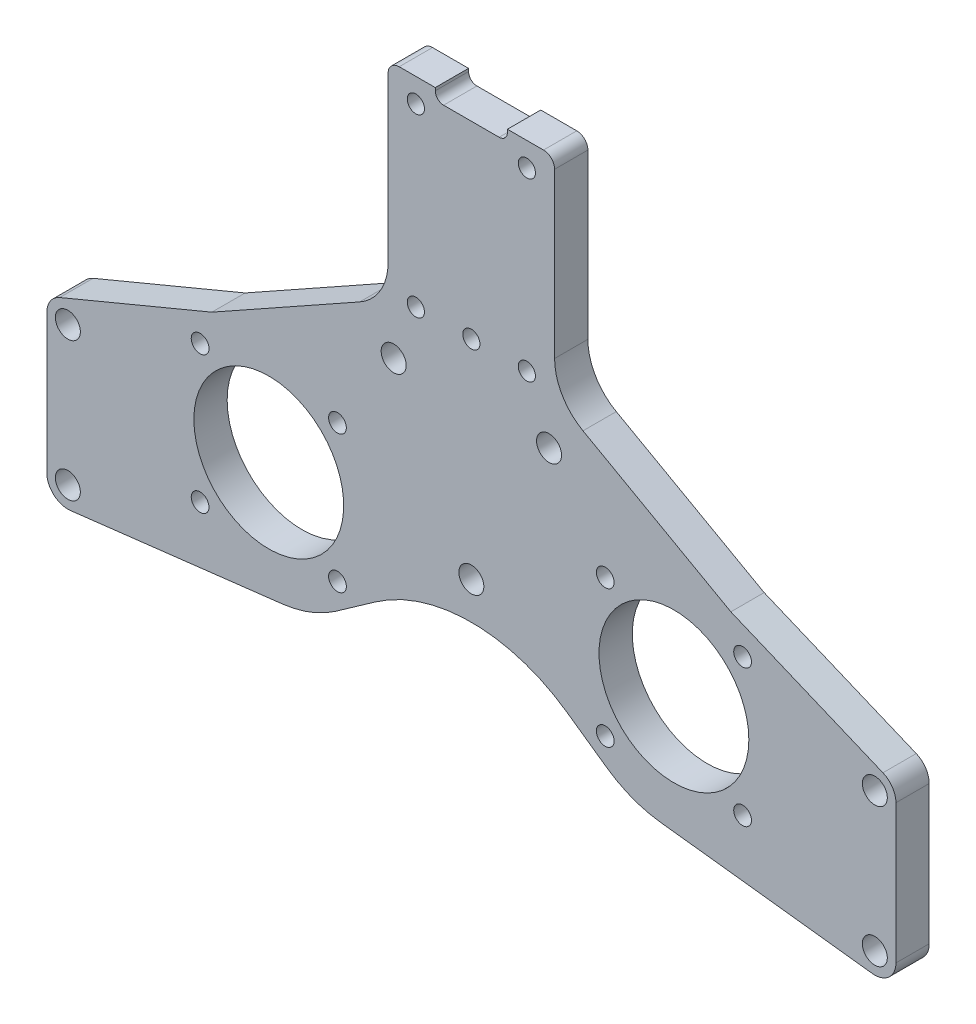
SolidWorks part; units mm, degrees
ref_plane "前视基准面" through (0, 0, 0) normal (0, 0, 1) x (1, 0, 0)
ref_plane "上视基准面" through (0, 0, 0) normal (0, 1, 0) x (1, 0, 0)
ref_plane "右视基准面" through (0, 0, 0) normal (1, 0, 0) x (0, 0, -1)
sketch "草图1" plane through (0, 0, 0) normal (0, 0, 1) x (1, 0, 0)
  line L0 (0, 0) -> (0, 27.5) construction
  line L1 (-14, 27.5) -> (14, 27.5) construction
  line L2 (-36.5, 0) -> (36.5, 0) construction
  line L3 (-20.1139, 33.2452) -> (-46.7609, 18.3225)
  line L4 (-24.4178, -17.1762) -> (-17.2603, -12.1414)
  line L5 (17.2603, -12.1414) -> (24.4178, -17.1762)
  line L6 (46.7609, 18.3225) -> (20.1139, 33.2452)
  line L7 (15, 41.9702) -> (15, 71.5)
  line L8 (13, 73.5) -> (-13, 73.5)
  line L9 (-15, 71.5) -> (-15, 41.9702)
  line L10 (0, 27.5) -> (0, 73.5) construction
  line L11 (24.1256, 12.3744) -> (36.5, 0) construction
  line L13 (10, 69.2) -> (-10, 69.2) construction
  line L14 (10, 69.2) -> (10, 37.5) construction
  line L15 (10, 37.5) -> (-10, 37.5) construction
  line L16 (-10, 69.2) -> (-10, 37.5) construction
  line L17 (10, 69.2) -> (-10, 37.5) construction
  line L18 (10, 37.5) -> (-10, 69.2) construction
  circle A0 centre (-14, 27.5) radius 2.25
  circle A1 centre (14, 27.5) radius 2.25
  circle A3 centre (36.5, 0) radius 13.5
  circle A6 centre (36.5, 0) radius 17.5 construction
  circle A7 centre (24.1256, 12.3744) radius 1.6
  circle A8 centre (48.8744, 12.3744) radius 1.6
  circle A9 centre (48.8744, -12.3744) radius 1.6
  circle A10 centre (24.1256, -12.3744) radius 1.6
  circle A11 centre (0, 0) radius 2.25
  circle A12 centre (-24.1256, -12.3744) radius 1.6
  circle A13 centre (-48.8744, -12.3744) radius 1.6
  circle A14 centre (-48.8744, 12.3744) radius 1.6
  circle A15 centre (-24.1256, 12.3744) radius 1.6
  circle A16 centre (-36.5, 0) radius 13.5
  arc A17 (24.4178, -17.1762) -> (46.7609, 18.3225) centre (36.5, 0) ccw
  arc A18 (-46.7609, 18.3225) -> (-24.4178, -17.1762) centre (-36.5, 0) ccw
  arc A19 (-17.2603, -12.1414) -> (17.2603, -12.1414) centre (0, -36.6787) cw
  arc A20 (20.1139, 33.2452) -> (15, 41.9702) centre (25, 41.9702) cw
  arc A21 (-20.1139, 33.2452) -> (-15, 41.9702) centre (-25, 41.9702) ccw
  arc A22 (-13, 73.5) -> (-15, 71.5) centre (-13, 71.5) ccw
  arc A23 (15, 71.5) -> (13, 73.5) centre (13, 71.5) ccw
  circle A24 centre (-10, 37.5) radius 1.55
  circle A25 centre (10, 37.5) radius 1.55
  circle A26 centre (-10, 69.2) radius 1.55
  circle A27 centre (10, 69.2) radius 1.55
  circle A28 centre (0, 37.5) radius 1.55
  point P22 (36.5, 0)
  point P42 (0, 53.35)
  point P51 (-15, 73.5)
  point P54 (15, 73.5)
  dimension "D3" = 4.5
  dimension "D5" = 27
  dimension "D6" = 35
  dimension "D8" = 3.2
  dimension "D9" = 21
  dimension "D10" = 30
  dimension "D15" = 10
  dimension "D16" = 2
  dimension "D20" = 3.1
  dimension "D1" = 27.5
  dimension "D2" = 28
  dimension "D4" = 73
  dimension "D11" = 45
  dimension "D12" = 46
  dimension "D13" = 30
  dimension "D14" = 8
  dimension "D17" = 31.7
  dimension "D18" = 20
  dimension "D19" = 10
  dimension "D7" = 4
extrude "凸台-拉伸1" add sketch "草图1" along normal blind 6
sketch "草图2" plane through (0, 0, 0) normal (0, 0, -1) x (-1, 0, 0)
  line L0 (0, -9.1) -> (0, 0) construction
  line L1 (-72.7, 3.4) -> (72.7, 3.4) construction
  line L2 (-72.7, 3.4) -> (-72.7, -21.6) construction
  line L3 (-72.7, -21.6) -> (72.7, -21.6) construction
  line L4 (72.7, 3.4) -> (72.7, -21.6) construction
  line L5 (-72.7, 3.4) -> (72.7, -21.6) construction
  line L6 (-72.7, -21.6) -> (72.7, 3.4) construction
  line L7 (34.0342, -20.8547) -> (72.2538, -25.3737)
  line L8 (76.5, -21.6) -> (76.5, 3.4)
  line L9 (74.1613, 6.9078) -> (46.7609, 18.3225)
  line L10 (-74.1613, 6.9078) -> (-46.7609, 18.3225)
  line L11 (-76.5, -21.6) -> (-76.5, 3.4)
  line L12 (-34.0342, -20.8547) -> (-72.2538, -25.3737)
  circle A0 centre (72.7, 3.4) radius 2.25
  circle A1 centre (72.7, -21.6) radius 2.25
  arc A4 (24.4178, -17.1762) -> (46.7609, 18.3225) centre (36.5, 0) ccw construction
  arc A5 (46.7609, 18.3225) -> (34.0342, -20.8547) centre (36.5, 0) cw
  arc A6 (76.5, 3.4) -> (74.1613, 6.9078) centre (72.7, 3.4) ccw
  arc A7 (72.2538, -25.3737) -> (76.5, -21.6) centre (72.7, -21.6) ccw
  circle A8 centre (-72.7, 3.4) radius 2.25
  circle A9 centre (-72.7, -21.6) radius 2.25
  arc A10 (-46.7609, 18.3225) -> (-34.0342, -20.8547) centre (-36.5, 0) ccw
  arc A11 (-76.5, 3.4) -> (-74.1613, 6.9078) centre (-72.7, 3.4) cw
  arc A12 (-72.2538, -25.3737) -> (-76.5, -21.6) centre (-72.7, -21.6) cw
  circle A13 centre (-72.7, 3.4) radius 2.1 construction
  point P0 (0, -9.1)
  dimension "D3" = 4.5
  dimension "D4" = 3.8
  dimension "D2" = 25
extrude "凸台-拉伸2" add sketch "草图2" against normal up to surface (6 mm away) up to face at (0, 28.5589, 6)
sketch "草图4" plane through (0, 0, 0) normal (0, 0, -1) x (-1, 0, 0)
  line L0 (-13, 73.5) -> (13, 73.5) construction
  line L1 (6.5, 73.5) -> (-6.5, 73.5)
  line L2 (6.5, 73.5) -> (6.5, 73)
  line L3 (5, 71.5) -> (-5, 71.5)
  line L4 (-6.5, 73.5) -> (-6.5, 73)
  line L5 (0, 64.35) -> (0, 71.5) construction
  arc A0 (6.5, 73) -> (5, 71.5) centre (5, 73) cw
  arc A1 (-5, 71.5) -> (-6.5, 73) centre (-5, 73) cw
  point P14 (-6.5, 71.5)
  dimension "D3" = 1.5
  dimension "D1" = 13
  dimension "D2" = 2
extrude "切除-拉伸2" cut sketch "草图4" against normal blind 10
